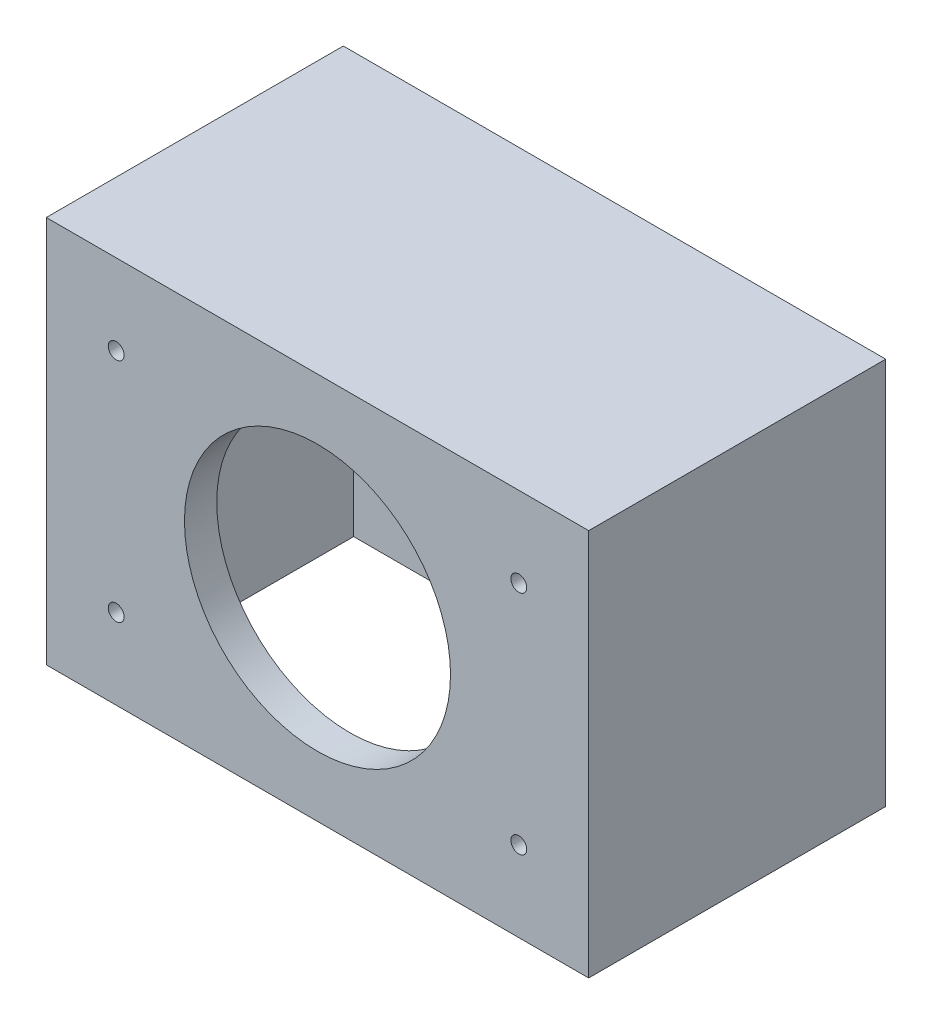
SolidWorks part; units mm, degrees
ref_plane "Front Plane" through (0, 0, 0) normal (0, 0, 1) x (1, 0, 0)
ref_plane "Top Plane" through (0, 0, 0) normal (0, 1, 0) x (1, 0, 0)
ref_plane "Right Plane" through (0, 0, 0) normal (1, 0, 0) x (0, 0, -1)
sketch "Sketch1" plane through (0, 0, 0) normal (0, 0, 1) x (1, 0, 0)
  line L1 (105, -75) -> (-105, -75)
  line L2 (105, -75) -> (105, 75)
  line L3 (105, 75) -> (-105, 75)
  line L4 (-105, -75) -> (-105, 75)
  line L5 (105, -75) -> (-105, 75) construction
  line L6 (105, 75) -> (-105, -75) construction
  point P0 (0, 0)
  dimension "D1" = 150
  dimension "D2" = 210
extrude "Boss-Extrude1" add sketch "Sketch1" along normal blind 115 contours L3 L4 L1 L2
sketch "Sketch3" plane through (0, -75, 0) normal (0, -1, 0) x (1, 0, 0)
  line L0 (0, 0) -> (0, 89.8335) construction
  line L1 (105, 0) -> (-105, 0) construction
  line L2 (105, 57.5) -> (-105, 57.5) construction
  line L3 (105, 115) -> (105, 0) construction
  line L4 (-105, 115) -> (-105, 0) construction
  line L6 (88.4868, 12.5) -> (-88.4868, 12.5)
  line L7 (88.4868, 12.5) -> (88.4868, 102.5)
  line L8 (88.4868, 102.5) -> (-88.4868, 102.5)
  line L9 (-88.4868, 12.5) -> (-88.4868, 102.5)
  line L10 (88.4868, 12.5) -> (-88.4868, 102.5) construction
  line L11 (88.4868, 102.5) -> (-88.4868, 12.5) construction
  point P10 (0, 57.5)
  dimension "D1" = 90
extrude "Cut-Extrude1" cut sketch "Sketch3" against normal blind 129
sketch "Sketch4" plane through (0, 0, 115) normal (0, 0, 1) x (1, 0, 0)
  line L0 (0, 0) -> (0, 67.172) construction
  line L1 (0, 0) -> (70.2154, 0) construction
  line L2 (0, 0) -> (-50.216, 0) construction
  line L3 (0, 0) -> (0, -30.4339) construction
  line L4 (0, 0) -> (77.9423, 43.8748) construction
  circle A0 centre (77.9423, 43.8748) radius 3.0725
  circle A1 centre (-77.9423, 43.8748) radius 3.0725
  circle A2 centre (-77.9423, -43.8748) radius 3.0725
  circle A3 centre (77.9423, -43.8748) radius 3.0725
  dimension "D1" = 6.145
extrude "Cut-Extrude2" cut sketch "Sketch4" against normal up to next
sketch "Sketch5" plane through (0, 0, 115) normal (0, 0, 1) x (1, 0, 0)
  circle A0 centre (0, 0) radius 51.5
extrude "Cut-Extrude3" cut sketch "Sketch5" against normal up to next
